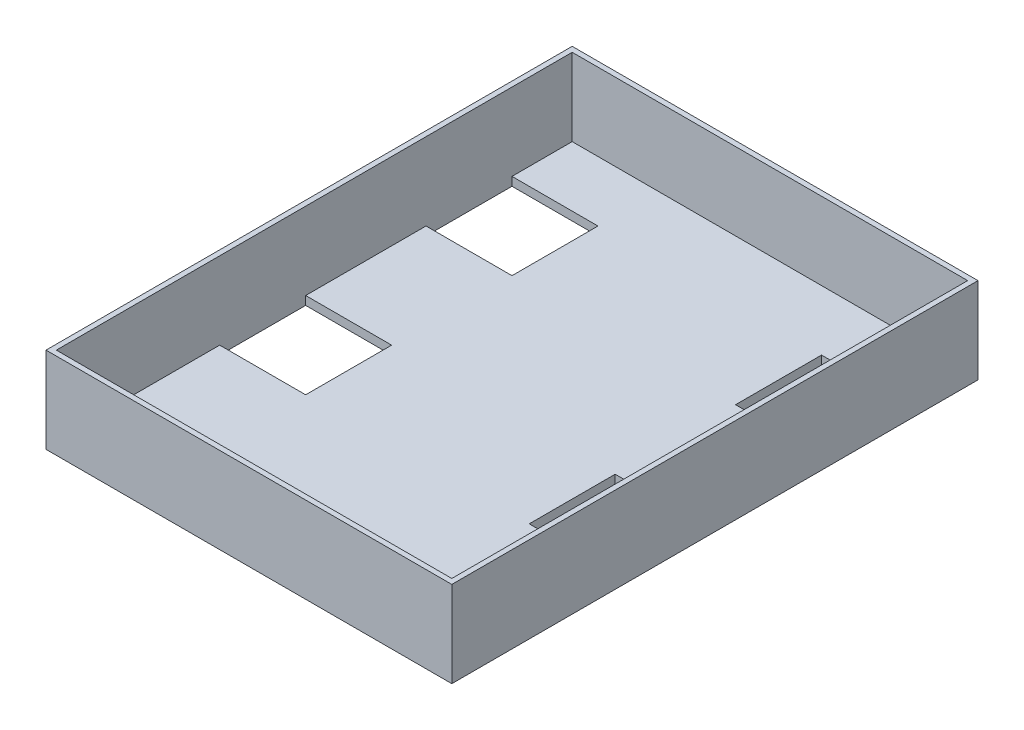
SolidWorks part; units mm, degrees
ref_plane "Front Plane" through (0, 0, 0) normal (0, 0, 1) x (1, 0, 0)
ref_plane "Top Plane" through (0, 0, 0) normal (0, 1, 0) x (1, 0, 0)
ref_plane "Right Plane" through (0, 0, 0) normal (1, 0, 0) x (0, 0, -1)
sketch "Sketch1" plane through (0, 0, 0) normal (0, 1, 0) x (1, 0, 0)
  line L0 (-115, 90) -> (115, 90) construction
  line L1 (-115, 150) -> (115, 150)
  line L2 (-115, 150) -> (-115, 115)
  line L3 (-115, -150) -> (115, -150)
  line L4 (115, 150) -> (115, 115)
  line L5 (-115, -30) -> (115, -30) construction
  line L6 (-115, 115) -> (-65, 115)
  line L7 (-65, 115) -> (-65, 65)
  line L8 (-65, 65) -> (-115, 65)
  line L9 (-115, 65) -> (-115, -5)
  line L10 (0, 150) -> (0, -150) construction
  line L11 (65, 65) -> (115, 65)
  line L12 (65, 115) -> (65, 65)
  line L13 (115, 115) -> (65, 115)
  line L14 (-115, -55) -> (-115, -150)
  line L15 (-115, -5) -> (-65, -5)
  line L17 (-115, -55) -> (-65, -55)
  line L18 (-65, -5) -> (-65, -55)
  line L19 (115, -55) -> (65, -55)
  line L20 (65, -5) -> (65, -55)
  line L21 (115, -5) -> (65, -5)
  line L22 (115, 65) -> (115, -5)
  line L23 (115, -55) -> (115, -150)
  point P4 (0, 150)
  dimension "D1" = 230
  dimension "D2" = 300
  dimension "D3" = 60
  dimension "D4" = 180
  dimension "D5" = 25
  dimension "D6" = 25
  dimension "D7" = 50
  dimension "D8" = 25
  dimension "D9" = 50
  dimension "D10" = 50
extrude "Boss-Extrude1" add sketch "Sketch1" along normal blind 5
sketch "Sketch2" plane through (0, 0, 0) normal (0, 1, 0) x (1, 0, 0)
  line L0 (115, 150) -> (-115, 150) construction
  line L1 (-115, 150) -> (115, 150)
  line L2 (-115, 150) -> (-115, -150)
  line L3 (-115, -150) -> (115, -150)
  line L4 (115, 150) -> (115, -150)
  line L5 (-115, 150) -> (-115, 115) construction
  line L6 (-118, 153) -> (-118, -153)
  line L7 (-118, -153) -> (118, -153)
  line L8 (118, 153) -> (118, -153)
  line L9 (-118, 153) -> (118, 153)
  dimension "D1" = 3
extrude "Boss-Extrude2" add sketch "Sketch2" along normal blind 50
